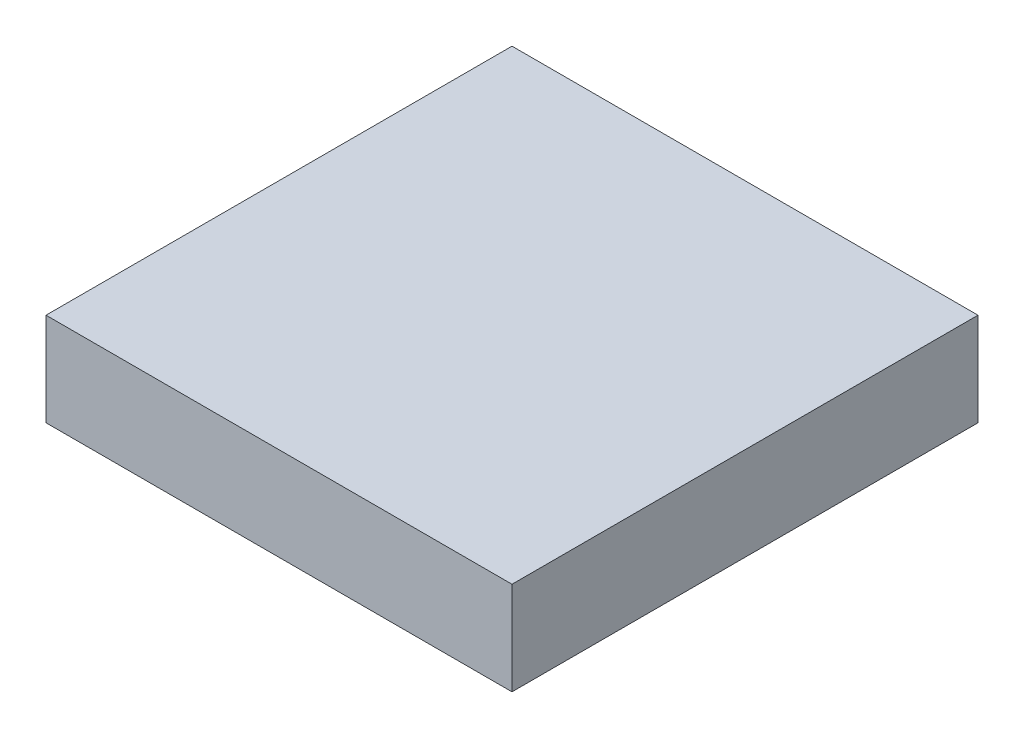
SolidWorks part; units mm, degrees
ref_plane "Front Plane" through (0, 0, 0) normal (0, 0, 1) x (1, 0, 0)
ref_plane "Top Plane" through (0, 0, 0) normal (0, 1, 0) x (1, 0, 0)
ref_plane "Right Plane" through (0, 0, 0) normal (1, 0, 0) x (0, 0, -1)
sketch "Sketch1" plane through (0, 0, 0) normal (0, 1, 0) x (1, 0, 0)
  line L1 (-8, -8) -> (8, -8)
  line L2 (-8, -8) -> (-8, 8)
  line L3 (-8, 8) -> (8, 8)
  line L4 (8, -8) -> (8, 8)
  line L5 (-8, -8) -> (8, 8) construction
  line L6 (-8, 8) -> (8, -8) construction
  point P0 (0, 0)
  dimension "D2" = 16
extrude "Boss-Extrude1" add sketch "Sketch1" along normal blind 3.2
